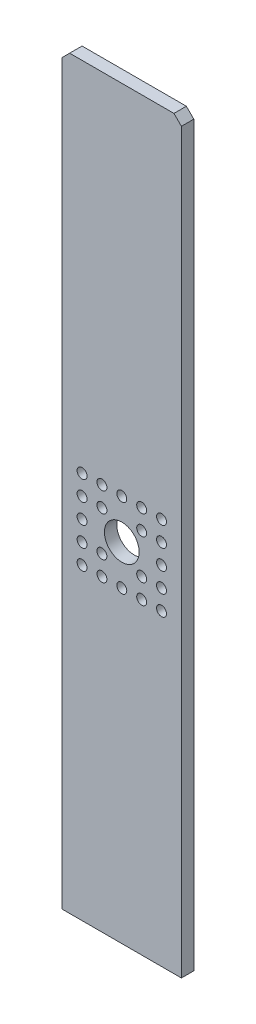
SolidWorks part; units mm, degrees
material "PMMA"
ref_plane "Front Plane" through (0, 0, 0) normal (0, 0, 1) x (1, 0, 0)
ref_plane "Top Plane" through (0, 0, 0) normal (0, 1, 0) x (1, 0, 0)
ref_plane "Right Plane" through (0, 0, 0) normal (1, 0, 0) x (0, 0, -1)
sketch "Sketch1" plane through (0, 0, 0) normal (0, 0, 1) x (1, 0, 0)
  line L0 (0, 0) -> (0, -300)
  line L1 (0, -300) -> (48, -300)
  line L2 (48, -300) -> (48, 0)
  line L3 (48, 0) -> (0, 0)
  line L4 (-41.1176, -160) -> (104.5651, -160) construction
  line L5 (24, 0) -> (24, -275.5734) construction
  line L6 (24, -160) -> (0, -136) construction
  circle A0 centre (24, -160) radius 7
  circle A1 centre (8, -144) radius 2
  circle A2 centre (16, -144) radius 2
  circle A3 centre (24, -144) radius 2
  circle A4 centre (32, -144) radius 2
  circle A5 centre (40, -144) radius 2
  circle A6 centre (16, -152) radius 2
  circle A8 centre (32, -152) radius 2
  circle A9 centre (40, -152) radius 2
  circle A13 centre (40, -160) radius 2
  circle A14 centre (16, -168) radius 2
  circle A16 centre (32, -168) radius 2
  circle A17 centre (40, -168) radius 2
  circle A18 centre (16, -176) radius 2
  circle A19 centre (24, -176) radius 2
  circle A20 centre (32, -176) radius 2
  circle A21 centre (40, -176) radius 2
  circle A22 centre (8, -152) radius 2
  circle A23 centre (8, -160) radius 2
  circle A24 centre (8, -168) radius 2
  circle A25 centre (8, -176) radius 2
  circle A26 centre (16, -160) radius 2 [skipped]
  circle A27 centre (24, -152) radius 2 [skipped]
  circle A28 centre (32, -160) radius 2 [skipped]
  circle A29 centre (24, -168) radius 2 [skipped]
  circle A30 centre (24, -160) radius 2 [skipped]
  dimension "D3" = 14
  dimension "D5" = 4
  dimension "D1" = 48
  dimension "D2" = 300
  dimension "D4" = 45
  dimension "D6" = 16
  dimension "D9" = 160
  dimension "D7" = 5
  dimension "D8" = 5
extrude "Boss-Extrude1" add sketch "Sketch1" along normal blind 5
chamfer "Chamfer1" distance 3 angle 45 2 edges at (0, 0, 2.5) (48, 0, 2.5)
